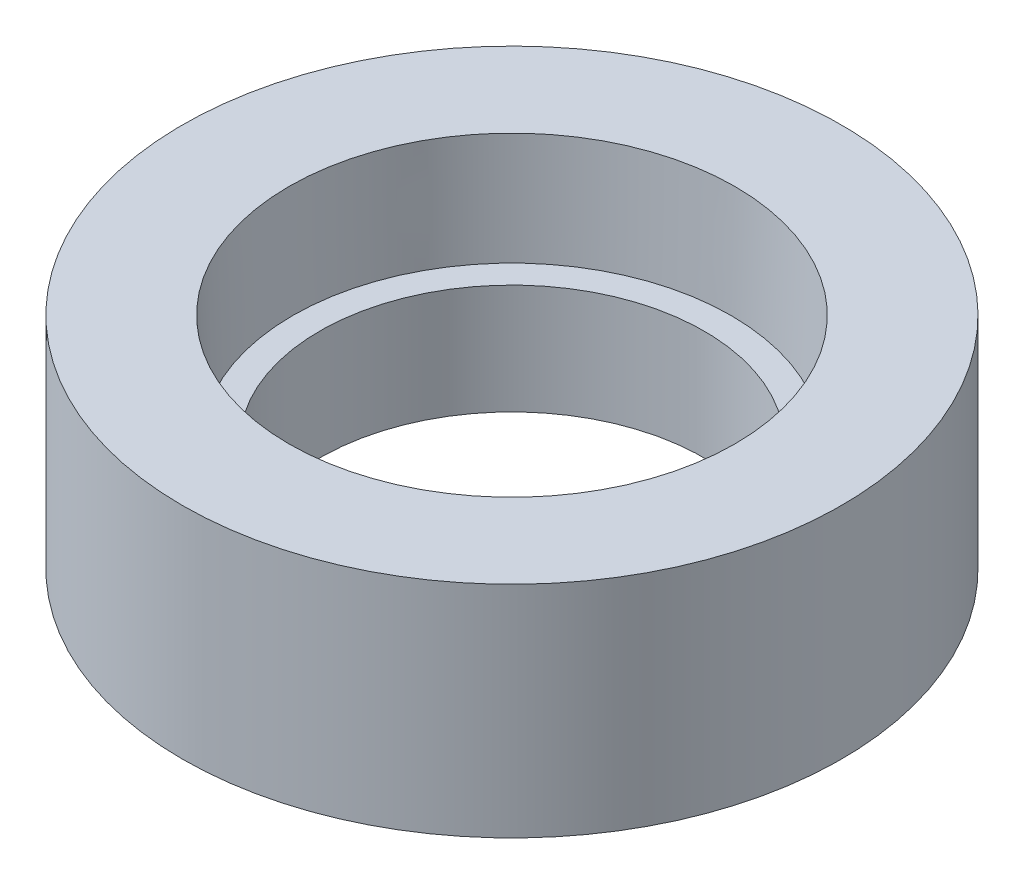
SolidWorks part; units mm, degrees
ref_plane "Front Plane" through (0, 0, 0) normal (0, 0, 1) x (1, 0, 0)
ref_plane "Top Plane" through (0, 0, 0) normal (0, 1, 0) x (1, 0, 0)
ref_plane "Right Plane" through (0, 0, 0) normal (1, 0, 0) x (0, 0, -1)
sketch "Sketch1" plane through (0, 0, 0) normal (0, 1, 0) x (1, 0, 0)
  circle A0 centre (0, 0) radius 38.1
  circle A1 centre (0, 0) radius 22.225
  dimension "D1" = 44.45
  dimension "D2" = 76.2
extrude "Boss-Extrude1" add sketch "Sketch1" along normal blind 25.4
sketch "Sketch2" plane through (0, 0, 0) normal (0, 1, 0) x (1, 0, 0)
  circle A0 centre (0, 0) radius 25.3365
  dimension "D1" = 50.673
extrude "Cut-Extrude1" cut sketch "Sketch2" along normal blind 12.7 draft 2 from offset 12.7 draft outward yes
